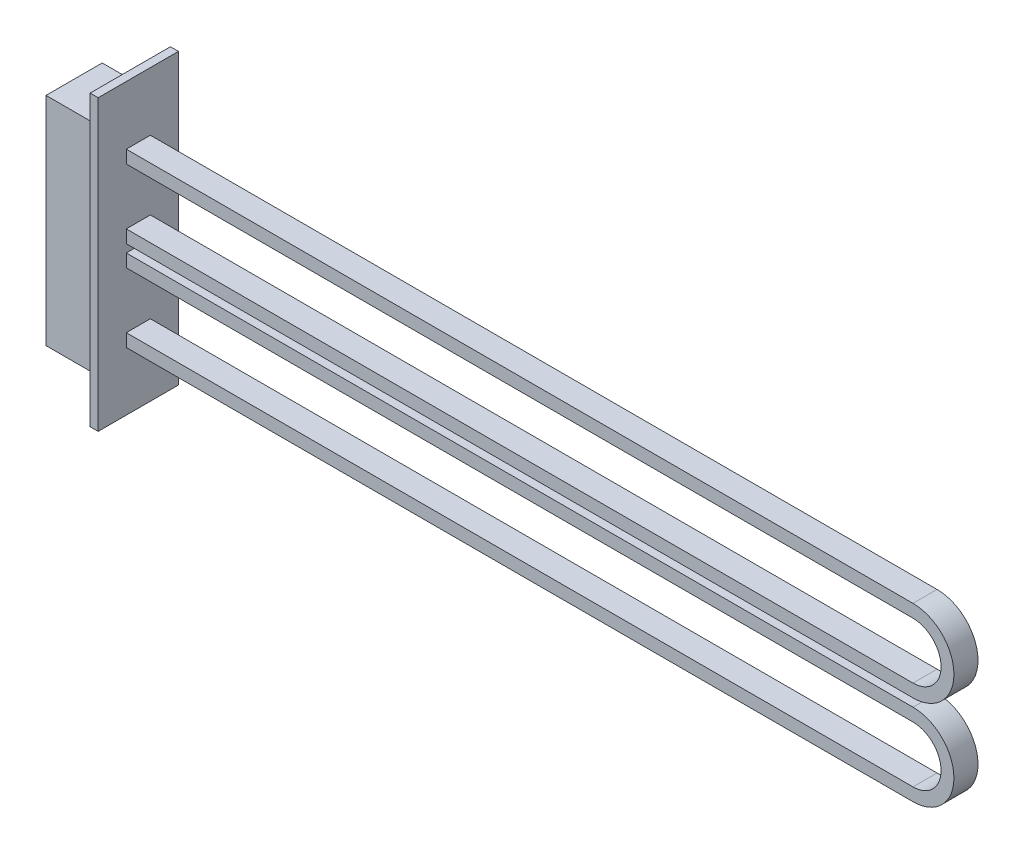
SolidWorks part; units mm, degrees
ref_plane "Alzado" through (0, 0, 0) normal (0, 0, 1) x (1, 0, 0)
ref_plane "Planta" through (0, 0, 0) normal (0, 1, 0) x (1, 0, 0)
ref_plane "Vista lateral" through (0, 0, 0) normal (1, 0, 0) x (0, 0, -1)
sketch "Sketch1" plane through (0, 0, 0) normal (0, 0, 1) x (1, 0, 0)
  line L4 (500, -43) -> (0, -43)
  line L5 (0, 8) -> (500, 8)
  line L6 (-619.3274, -45.5) -> (49380.6726, -45.5) construction
  line L11 (8, 0) -> (500, 0)
  line L12 (500, -35) -> (8, -35)
  line L18 (8, -56) -> (0, -56)
  line L20 (8, 0) -> (8, -35) construction
  line L21 (0, 8) -> (0, -43) construction
  line L22 (8, 0) -> (0, 0)
  line L23 (8, -35) -> (0, -35)
  line L24 (0, 8) -> (0, 0)
  line L25 (0, -35) -> (0, -43)
  line L34 (500, -56) -> (8, -56)
  line L35 (8, -91) -> (500, -91)
  line L36 (8, -91) -> (0, -91)
  line L37 (0, -99) -> (0, -91)
  line L38 (0, -99) -> (500, -99)
  line L39 (500, -48) -> (0, -48)
  line L40 (0, -56) -> (0, -48)
  arc A1 (500, 8) -> (500, -43) centre (500, -17.5) cw
  arc A4 (500, 0) -> (500, -35) centre (500, -17.5) cw
  arc A7 (500, -91) -> (500, -56) centre (500, -73.5) ccw
  arc A8 (500, -99) -> (500, -48) centre (500, -73.5) ccw
  point P7 (-7.7229, 7.7229)
  point P8 (-7.7229, -25)
  dimension "D3" = 500
  dimension "D4" = 2.5
  dimension "D5" = 35
  dimension "D2" = 17.5
  dimension "D1" = 8
extrude "Boss-Extrude1" add sketch "Sketch1" along normal blind 15
sketch "Sketch3" plane through (0, 0, 0) normal (-1, 0, 0) x (0, 0, 1)
  line L0 (0, 4) -> (15, 4) construction
  line L1 (15, 8) -> (0, 8) construction
  line L3 (7.5, -43) -> (7.5, 8) construction
  line L4 (15, -43) -> (0, -43) construction
  line L5 (0, 8) -> (0, 0) construction
  line L6 (15, 8) -> (15, 0) construction
  line L7 (0, -17.5) -> (15, -17.5) construction
  line L8 (15, -35) -> (15, 0) construction
  line L9 (7.5, -99) -> (7.5, 8) construction
  line L10 (15, -99) -> (0, -99) construction
  line L11 (0, -45.5) -> (15, -45.5) construction
  circle A0 centre (7.5, 4) radius 2.5
  circle A1 centre (7.5, -39) radius 2.5
  circle A2 centre (7.5, -52) radius 2.5
  circle A3 centre (7.5, -95) radius 2.5
  point P19 (7.5, -17.5)
  point P25 (7.5, -45.5)
  dimension "D1" = 5
extrude "Boss-Extrude2" add sketch "Sketch3" along normal blind 15 separate body
ref_plane "Plane1" through (10, 0, 0) normal (1, 0, 0) x (0, 0, -1)
sketch "Sketch5" plane through (10, 0, 0) normal (1, 0, 0) x (0, 0, -1)
  line L0 (-7.5, 8) -> (-7.5, -99) construction
  line L1 (-15, 8) -> (0, 8) construction
  line L2 (-15, -99) -> (0, -99) construction
  line L4 (17.5, 44.5) -> (-32.5, 44.5)
  line L5 (17.5, 44.5) -> (17.5, -135.5)
  line L6 (17.5, -135.5) -> (-32.5, -135.5)
  line L7 (-32.5, 44.5) -> (-32.5, -135.5)
  line L8 (17.5, 44.5) -> (-32.5, -135.5) construction
  line L9 (17.5, -135.5) -> (-32.5, 44.5) construction
  point P7 (-7.5, -45.5)
  dimension "D1" = 50
  dimension "D2" = 180
extrude "Boss-Extrude3" add sketch "Sketch5" against normal blind 5
sketch "Sketch6" plane through (5, 0, 0) normal (-1, 0, 0) x (0, 0, 1)
  line L0 (7.5, -135.5) -> (7.5, 44.5) construction
  line L1 (32.5, -135.5) -> (-17.5, -135.5) construction
  line L2 (-17.5, 44.5) -> (32.5, 44.5) construction
sketch "Sketch7" plane through (5, 0, 0) normal (-1, 0, 0) x (0, 0, 1)
  line L0 (7.5, -135.5) -> (7.5, 44.5) construction
  line L1 (-10, 22) -> (25, 22)
  line L2 (-10, 22) -> (-10, -113)
  line L3 (-10, -113) -> (25, -113)
  line L4 (25, 22) -> (25, -113)
  line L5 (-10, 22) -> (25, -113) construction
  line L6 (-10, -113) -> (25, 22) construction
  point P0 (7.5, -45.5)
  dimension "D1" = 35
  dimension "D2" = 135
extrude "Boss-Extrude4" add sketch "Sketch7" along normal blind 35 separate body
